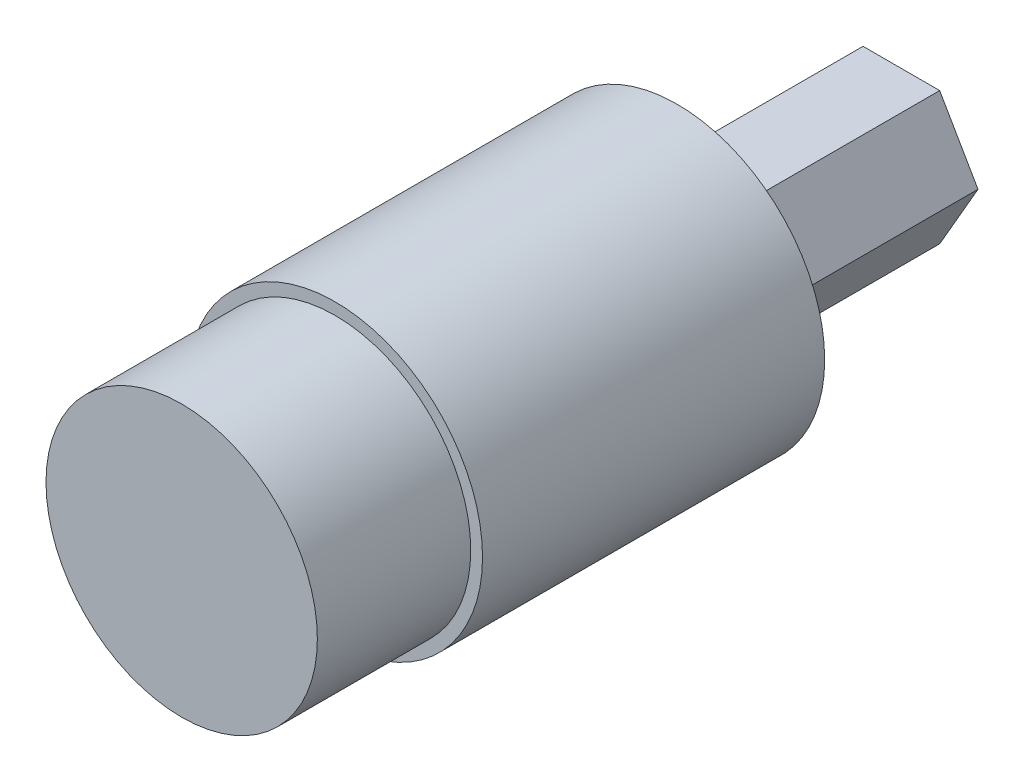
SolidWorks part; units mm, degrees
ref_plane "PL-01 Front" through (0, 0, 0) normal (0, 0, 1) x (1, 0, 0)
ref_plane "PL-02 Top" through (0, 0, 0) normal (0, 1, 0) x (1, 0, 0)
ref_plane "PL-03 Right" through (0, 0, 0) normal (1, 0, 0) x (0, 0, -1)
sketch "Sketch2" plane through (0, 0, 0) normal (0, 0, 1) x (1, 0, 0)
  circle A0 centre (0, 0) radius 15.875
  dimension "D1" = 31.75
extrude "Boss-Extrude1" add sketch "Sketch2" along normal blind 53.34
sketch "Sketch3" plane through (0, 0, 0) normal (0, 0, -1) x (-1, 0, 0)
  line L1 (8.2489, 0) -> (4.1244, 7.1438)
  line L2 (4.1244, 7.1438) -> (-4.1244, 7.1438)
  line L3 (-4.1244, 7.1438) -> (-8.2489, 0)
  line L4 (-8.2489, 0) -> (-4.1244, -7.1438)
  line L5 (-4.1244, -7.1438) -> (4.1244, -7.1438)
  line L6 (4.1244, -7.1438) -> (8.2489, 0)
  circle A0 centre (0, 0) radius 7.1437 construction
  circle A1 centre (0, 0) radius 4.3053
  dimension "D2" = 8.6106
  dimension "D1" = 14.2875
extrude "Boss-Extrude2" add sketch "Sketch3" along normal blind 24.13
sketch "Sketch4" plane through (0, 0, 0) normal (0, 1, 0) x (1, 0, 0)
  circle A0 centre (1.4757, -26.4362) radius 3.175
  dimension "D1" = 6.35
extrude "Boss-Extrude3" add sketch "Sketch4" against normal blind 16.51
sketch "Sketch5" plane through (0, 0, 53.34) normal (0, 0, 1) x (1, 0, 0)
  circle A2 centre (0, 0) radius 14.605
  circle A3 centre (0, 0) radius 14.605
  dimension "D1" = 1.27
extrude "Cut-Extrude1" cut sketch "Sketch5" against normal blind 16.51 flip side to cut
